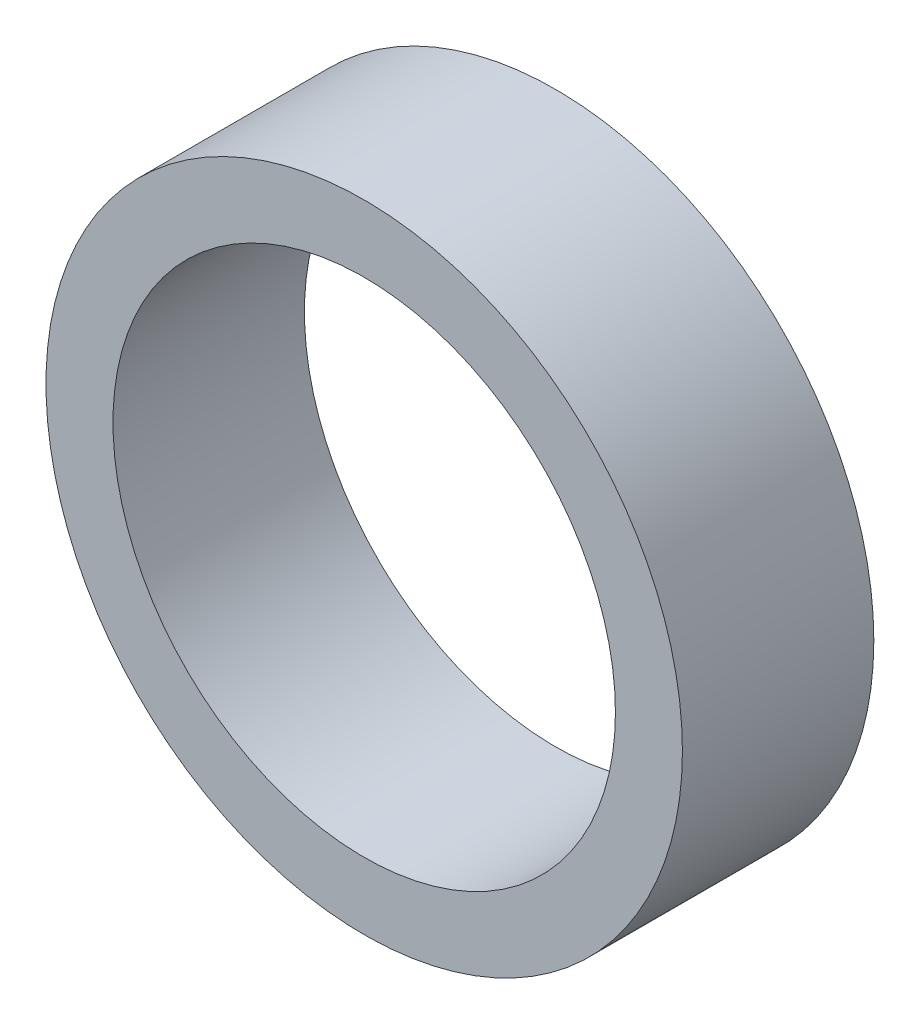
SolidWorks part; units mm, degrees
ref_plane "Front Plane" through (0, 0, 0) normal (0, 0, 1) x (1, 0, 0)
ref_plane "Top Plane" through (0, 0, 0) normal (0, 1, 0) x (1, 0, 0)
ref_plane "Right Plane" through (0, 0, 0) normal (1, 0, 0) x (0, 0, -1)
sketch "Sketch1" plane through (0, 0, 3) normal (0, 0, 1) x (1, 0, 0)
  circle A0 centre (33, 0) radius 3.325
  circle A1 centre (33, 0) radius 2.625
  dimension "D1" = 6.65
  dimension "D2" = 5.25
extrude "Boss-Extrude1" add sketch "Sketch1" along normal blind 2 from offset 5
equation "\"RingPinShaft\"= 5.05"
equation "\"CenterBearingOut\"=32.05"
equation "\"OutputBearingOut\"=37.05"
equation "\"RingPostIn\"=5.15"
equation "\"CamBearingOut\"=15.1"
equation "\"DiskOutputShaft\"=10.1"
equation "\"CenterShaft\"=25.2"
equation "\"Eccentricity\"=2"
equation "\"CycCamShaft\"=10.05"
equation "\"m3Thru\"=3.15"
equation "\"m3Insert\"=4.2"
equation "\"D2@Sketch1\"=\"RingPostIn\"+0.1"
equation "\"D1@Sketch1\"=\"RingPostIn\"+1.5"
